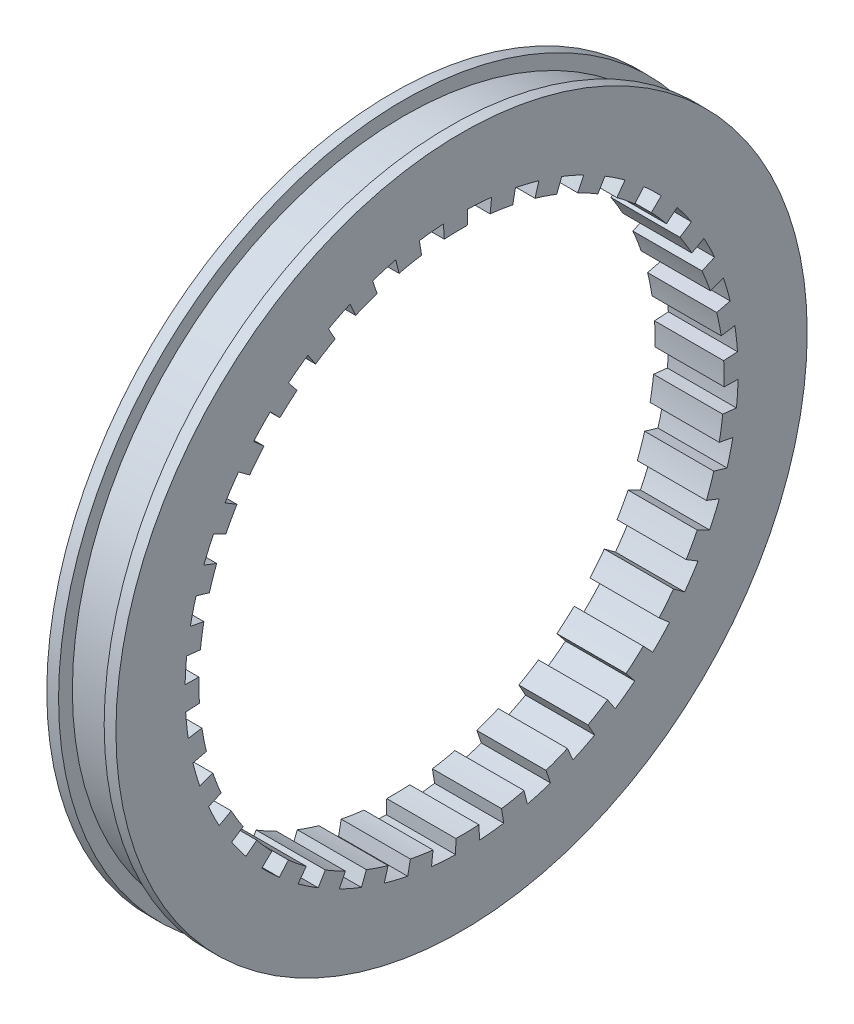
SolidWorks part; units mm, degrees
ref_plane "Front Plane" through (0, 0, 0) normal (0, 0, 1) x (1, 0, 0)
ref_plane "Top Plane" through (0, 0, 0) normal (0, 1, 0) x (1, 0, 0)
ref_plane "Right Plane" through (0, 0, 0) normal (1, 0, 0) x (0, 0, -1)
sketch "Sketch1" plane through (0, 0, 0) normal (1, 0, 0) x (0, 0, -1)
  circle A0 centre (0, 0) radius 20
  dimension "D1" = 40
extrude "Boss-Extrude1" add sketch "Sketch1" along normal blind 4
sketch "Sketch2" plane through (4, 0, 0) normal (1, 0, 0) x (0, 0, -1)
  line L0 (-17.0423, 8.4) -> (-17.9393, 8.8421)
  line L1 (-16.2453, 9.8534) -> (-17.1004, 10.372)
  circle A1 centre (0, 0) radius 20 construction
  circle A2 centre (0, 0) radius 19
  arc A3 (-16.2453, 9.8534) -> (-17.0423, 8.4) centre (0, 0) ccw
  arc A4 (-17.1004, 10.372) -> (-17.9393, 8.8421) centre (0, 0) ccw
  dimension "D2" = 5
  dimension "D1" = 1
extrude "Cut-Extrude1" cut sketch "Sketch2" against normal through all
sketch "Sketch3" plane through (4, 0, 0) normal (1, 0, 0) x (0, 0, -1)
  line L0 (-20, 0) -> (0, 0)
  arc A0 (-17.9393, 8.8421) -> (-17.1004, 10.372) centre (0, 0) ccw construction
ref_axis "Axis1" through (4, 0, 0) along (1, 0, 0)
pattern_circular "CirPattern2" count 36 over 360 about axis through (0, 0, 0) along (1, 0, 0) of "Cut-Extrude1"
sketch "Sketch5" plane through (4, 0, 0) normal (1, 0, 0) x (0, 0, -1)
  line L72 (-10.5591, 15.7958) -> (-11.1148, 16.6271)
  line L73 (-12.5217, 15.5951) -> (-11.8956, 14.8154)
  line L74 (-13.1416, 13.7222) -> (-13.8332, 14.4444)
  line L75 (-15.0395, 13.1838) -> (-14.2875, 12.5246)
  line L76 (-15.3248, 11.2317) -> (-16.1313, 11.8229)
  line L77 (-17.1004, 10.372) -> (-16.2453, 9.8534)
  line L78 (-17.0423, 8.4) -> (-17.9393, 8.8421)
  line L79 (-18.6416, 7.2449) -> (-17.7096, 6.8827)
  line L80 (-18.242, 5.313) -> (-19.2021, 5.5926)
  line L81 (-19.6165, 3.8978) -> (-18.6357, 3.7029)
  line L82 (-18.8875, 2.0646) -> (-19.8816, 2.1733)
  line L83 (-19.9953, 0.4322) -> (-18.9956, 0.4106)
  line L84 (-18.9591, -1.2466) -> (-19.9569, -1.3122)
  line L85 (-19.7666, -3.0465) -> (-18.7783, -2.8942)
  line L86 (-18.4546, -4.5198) -> (-19.4259, -4.7577)
  line L87 (-18.9373, -6.4327) -> (-17.9904, -6.111)
  line L88 (-17.3893, -7.6558) -> (-18.3046, -8.0587)
  line L89 (-17.5326, -9.6234) -> (-16.6559, -9.1422)
  line L90 (-15.7958, -10.5591) -> (-16.6271, -11.1148)
  line L91 (-15.5951, -12.5217) -> (-14.8154, -11.8956)
  line L92 (-13.7222, -13.1416) -> (-14.4444, -13.8332)
  line L93 (-13.1838, -15.0395) -> (-12.5246, -14.2875)
  line L94 (-11.2317, -15.3248) -> (-11.8229, -16.1313)
  line L95 (-10.372, -17.1004) -> (-9.8534, -16.2453)
  line L96 (-8.4, -17.0423) -> (-8.8421, -17.9393)
  line L97 (-7.2449, -18.6416) -> (-6.8827, -17.7096)
  line L98 (-5.313, -18.242) -> (-5.5926, -19.2021)
  line L99 (-3.8978, -19.6165) -> (-3.7029, -18.6357)
  line L100 (-2.0646, -18.8875) -> (-2.1733, -19.8816)
  line L101 (-0.4322, -19.9953) -> (-0.4106, -18.9956)
  line L102 (1.2466, -18.9591) -> (1.3122, -19.9569)
  line L103 (3.0465, -19.7666) -> (2.8942, -18.7783)
  line L104 (4.5198, -18.4546) -> (4.7577, -19.4259)
  line L105 (6.4327, -18.9373) -> (6.111, -17.9904)
  line L106 (7.6558, -17.3893) -> (8.0587, -18.3046)
  line L107 (9.6234, -17.5326) -> (9.1422, -16.6559)
  line L108 (10.5591, -15.7958) -> (11.1148, -16.6271)
  line L109 (12.5217, -15.5951) -> (11.8956, -14.8154)
  line L110 (13.1416, -13.7222) -> (13.8332, -14.4444)
  line L111 (15.0395, -13.1838) -> (14.2875, -12.5246)
  line L112 (15.3248, -11.2317) -> (16.1313, -11.8229)
  line L113 (17.1004, -10.372) -> (16.2453, -9.8534)
  line L114 (17.0423, -8.4) -> (17.9393, -8.8421)
  line L115 (18.6416, -7.2449) -> (17.7096, -6.8827)
  line L116 (18.242, -5.313) -> (19.2021, -5.5926)
  line L117 (19.6165, -3.8978) -> (18.6357, -3.7029)
  line L118 (18.8875, -2.0646) -> (19.8816, -2.1733)
  line L119 (19.9953, -0.4322) -> (18.9956, -0.4106)
  line L120 (18.9591, 1.2466) -> (19.9569, 1.3122)
  line L121 (19.7666, 3.0465) -> (18.7783, 2.8942)
  line L122 (18.4546, 4.5198) -> (19.4259, 4.7577)
  line L123 (18.9373, 6.4327) -> (17.9904, 6.111)
  line L124 (17.3893, 7.6558) -> (18.3046, 8.0587)
  line L125 (17.5326, 9.6234) -> (16.6559, 9.1422)
  line L126 (15.7958, 10.5591) -> (16.6271, 11.1148)
  line L127 (15.5951, 12.5217) -> (14.8154, 11.8956)
  line L128 (13.7222, 13.1416) -> (14.4444, 13.8332)
  line L129 (13.1838, 15.0395) -> (12.5246, 14.2875)
  line L130 (11.2317, 15.3248) -> (11.8229, 16.1313)
  line L131 (10.372, 17.1004) -> (9.8534, 16.2453)
  line L132 (8.4, 17.0423) -> (8.8421, 17.9393)
  line L133 (7.2449, 18.6416) -> (6.8827, 17.7096)
  line L134 (5.313, 18.242) -> (5.5926, 19.2021)
  line L135 (3.8978, 19.6165) -> (3.7029, 18.6357)
  line L136 (2.0646, 18.8875) -> (2.1733, 19.8816)
  line L137 (0.4322, 19.9953) -> (0.4106, 18.9956)
  line L138 (-1.2466, 18.9591) -> (-1.3122, 19.9569)
  line L139 (-3.0465, 19.7666) -> (-2.8942, 18.7783)
  line L140 (-4.5198, 18.4546) -> (-4.7577, 19.4259)
  line L141 (-6.4327, 18.9373) -> (-6.111, 17.9904)
  line L142 (-7.6558, 17.3893) -> (-8.0587, 18.3046)
  line L143 (-9.6234, 17.5326) -> (-9.1422, 16.6559)
  line L144 (-10.5591, 15.7958) -> (-11.1148, 16.6271)
  line L145 (-12.5217, 15.5951) -> (-11.8956, 14.8154)
  line L146 (-13.1416, 13.7222) -> (-13.8332, 14.4444)
  line L147 (-15.0395, 13.1838) -> (-14.2875, 12.5246)
  line L148 (-15.3248, 11.2317) -> (-16.1313, 11.8229)
  line L149 (-17.1004, 10.372) -> (-16.2453, 9.8534)
  line L150 (-17.0423, 8.4) -> (-17.9393, 8.8421)
  line L151 (-18.6416, 7.2449) -> (-17.7096, 6.8827)
  line L152 (-18.242, 5.313) -> (-19.2021, 5.5926)
  line L153 (-19.6165, 3.8978) -> (-18.6357, 3.7029)
  line L154 (-18.8875, 2.0646) -> (-19.8816, 2.1733)
  line L155 (-19.9953, 0.4322) -> (-18.9956, 0.4106)
  line L156 (-18.9591, -1.2466) -> (-19.9569, -1.3122)
  line L157 (-19.7666, -3.0465) -> (-18.7783, -2.8942)
  line L158 (-18.4546, -4.5198) -> (-19.4259, -4.7577)
  line L159 (-18.9373, -6.4327) -> (-17.9904, -6.111)
  line L160 (-17.3893, -7.6558) -> (-18.3046, -8.0587)
  line L161 (-17.5326, -9.6234) -> (-16.6559, -9.1422)
  line L162 (-15.7958, -10.5591) -> (-16.6271, -11.1148)
  line L163 (-15.5951, -12.5217) -> (-14.8154, -11.8956)
  line L164 (-13.7222, -13.1416) -> (-14.4444, -13.8332)
  line L165 (-13.1838, -15.0395) -> (-12.5246, -14.2875)
  line L166 (-11.2317, -15.3248) -> (-11.8229, -16.1313)
  line L167 (-10.372, -17.1004) -> (-9.8534, -16.2453)
  line L168 (-8.4, -17.0423) -> (-8.8421, -17.9393)
  line L169 (-7.2449, -18.6416) -> (-6.8827, -17.7096)
  line L170 (-5.313, -18.242) -> (-5.5926, -19.2021)
  line L171 (-3.8978, -19.6165) -> (-3.7029, -18.6357)
  line L172 (-2.0646, -18.8875) -> (-2.1733, -19.8816)
  line L173 (-0.4322, -19.9953) -> (-0.4106, -18.9956)
  line L174 (1.2466, -18.9591) -> (1.3122, -19.9569)
  line L175 (3.0465, -19.7666) -> (2.8942, -18.7783)
  line L176 (4.5198, -18.4546) -> (4.7577, -19.4259)
  line L177 (6.4327, -18.9373) -> (6.111, -17.9904)
  line L178 (7.6558, -17.3893) -> (8.0587, -18.3046)
  line L179 (9.6234, -17.5326) -> (9.1422, -16.6559)
  line L180 (10.5591, -15.7958) -> (11.1148, -16.6271)
  line L181 (12.5217, -15.5951) -> (11.8956, -14.8154)
  line L182 (13.1416, -13.7222) -> (13.8332, -14.4444)
  line L183 (15.0395, -13.1838) -> (14.2875, -12.5246)
  line L184 (15.3248, -11.2317) -> (16.1313, -11.8229)
  line L185 (17.1004, -10.372) -> (16.2453, -9.8534)
  line L186 (17.0423, -8.4) -> (17.9393, -8.8421)
  line L187 (18.6416, -7.2449) -> (17.7096, -6.8827)
  line L188 (18.242, -5.313) -> (19.2021, -5.5926)
  line L189 (19.6165, -3.8978) -> (18.6357, -3.7029)
  line L190 (18.8875, -2.0646) -> (19.8816, -2.1733)
  line L191 (19.9953, -0.4322) -> (18.9956, -0.4106)
  line L192 (18.9591, 1.2466) -> (19.9569, 1.3122)
  line L193 (19.7666, 3.0465) -> (18.7783, 2.8942)
  line L194 (18.4546, 4.5198) -> (19.4259, 4.7577)
  line L195 (18.9373, 6.4327) -> (17.9904, 6.111)
  line L196 (17.3893, 7.6558) -> (18.3046, 8.0587)
  line L197 (17.5326, 9.6234) -> (16.6559, 9.1422)
  line L198 (15.7958, 10.5591) -> (16.6271, 11.1148)
  line L199 (15.5951, 12.5217) -> (14.8154, 11.8956)
  line L200 (13.7222, 13.1416) -> (14.4444, 13.8332)
  line L201 (13.1838, 15.0395) -> (12.5246, 14.2875)
  line L202 (11.2317, 15.3248) -> (11.8229, 16.1313)
  line L203 (10.372, 17.1004) -> (9.8534, 16.2453)
  line L204 (8.4, 17.0423) -> (8.8421, 17.9393)
  line L205 (7.2449, 18.6416) -> (6.8827, 17.7096)
  line L206 (5.313, 18.242) -> (5.5926, 19.2021)
  line L207 (3.8978, 19.6165) -> (3.7029, 18.6357)
  line L208 (2.0646, 18.8875) -> (2.1733, 19.8816)
  line L209 (0.4322, 19.9953) -> (0.4106, 18.9956)
  line L210 (-1.2466, 18.9591) -> (-1.3122, 19.9569)
  line L211 (-3.0465, 19.7666) -> (-2.8942, 18.7783)
  line L212 (-4.5198, 18.4546) -> (-4.7577, 19.4259)
  line L213 (-6.4327, 18.9373) -> (-6.111, 17.9904)
  line L214 (-7.6558, 17.3893) -> (-8.0587, 18.3046)
  line L215 (-9.6234, 17.5326) -> (-9.1422, 16.6559)
  circle A1 centre (0, 0) radius 25
  arc A72 (-11.1148, 16.6271) -> (-12.5217, 15.5951) centre (0, 0) ccw
  arc A73 (-11.8956, 14.8154) -> (-13.1416, 13.7222) centre (0, 0) ccw
  arc A74 (-13.8332, 14.4444) -> (-15.0395, 13.1838) centre (0, 0) ccw
  arc A75 (-14.2875, 12.5246) -> (-15.3248, 11.2317) centre (0, 0) ccw
  arc A76 (-16.1313, 11.8229) -> (-17.1004, 10.372) centre (0, 0) ccw
  arc A77 (-16.2453, 9.8534) -> (-17.0423, 8.4) centre (0, 0) ccw
  arc A78 (-17.9393, 8.8421) -> (-18.6416, 7.2449) centre (0, 0) ccw
  arc A79 (-17.7096, 6.8827) -> (-18.242, 5.313) centre (0, 0) ccw
  arc A80 (-19.2021, 5.5926) -> (-19.6165, 3.8978) centre (0, 0) ccw
  arc A81 (-18.6357, 3.7029) -> (-18.8875, 2.0646) centre (0, 0) ccw
  arc A82 (-19.8816, 2.1733) -> (-19.9953, 0.4322) centre (0, 0) ccw
  arc A83 (-18.9956, 0.4106) -> (-18.9591, -1.2466) centre (0, 0) ccw
  arc A84 (-19.9569, -1.3122) -> (-19.7666, -3.0465) centre (0, 0) ccw
  arc A85 (-18.7783, -2.8942) -> (-18.4546, -4.5198) centre (0, 0) ccw
  arc A86 (-19.4259, -4.7577) -> (-18.9373, -6.4327) centre (0, 0) ccw
  arc A87 (-17.9904, -6.111) -> (-17.3893, -7.6558) centre (0, 0) ccw
  arc A88 (-18.3046, -8.0587) -> (-17.5326, -9.6234) centre (0, 0) ccw
  arc A89 (-16.6559, -9.1422) -> (-15.7958, -10.5591) centre (0, 0) ccw
  arc A90 (-16.6271, -11.1148) -> (-15.5951, -12.5217) centre (0, 0) ccw
  arc A91 (-14.8154, -11.8956) -> (-13.7222, -13.1416) centre (0, 0) ccw
  arc A92 (-14.4444, -13.8332) -> (-13.1838, -15.0395) centre (0, 0) ccw
  arc A93 (-12.5246, -14.2875) -> (-11.2317, -15.3248) centre (0, 0) ccw
  arc A94 (-11.8229, -16.1313) -> (-10.372, -17.1004) centre (0, 0) ccw
  arc A95 (-9.8534, -16.2453) -> (-8.4, -17.0423) centre (0, 0) ccw
  arc A96 (-8.8421, -17.9393) -> (-7.2449, -18.6416) centre (0, 0) ccw
  arc A97 (-6.8827, -17.7096) -> (-5.313, -18.242) centre (0, 0) ccw
  arc A98 (-5.5926, -19.2021) -> (-3.8978, -19.6165) centre (0, 0) ccw
  arc A99 (-3.7029, -18.6357) -> (-2.0646, -18.8875) centre (0, 0) ccw
  arc A100 (-2.1733, -19.8816) -> (-0.4322, -19.9953) centre (0, 0) ccw
  arc A101 (-0.4106, -18.9956) -> (1.2466, -18.9591) centre (0, 0) ccw
  arc A102 (1.3122, -19.9569) -> (3.0465, -19.7666) centre (0, 0) ccw
  arc A103 (2.8942, -18.7783) -> (4.5198, -18.4546) centre (0, 0) ccw
  arc A104 (4.7577, -19.4259) -> (6.4327, -18.9373) centre (0, 0) ccw
  arc A105 (6.111, -17.9904) -> (7.6558, -17.3893) centre (0, 0) ccw
  arc A106 (8.0587, -18.3046) -> (9.6234, -17.5326) centre (0, 0) ccw
  arc A107 (9.1422, -16.6559) -> (10.5591, -15.7958) centre (0, 0) ccw
  arc A108 (11.1148, -16.6271) -> (12.5217, -15.5951) centre (0, 0) ccw
  arc A109 (11.8956, -14.8154) -> (13.1416, -13.7222) centre (0, 0) ccw
  arc A110 (13.8332, -14.4444) -> (15.0395, -13.1838) centre (0, 0) ccw
  arc A111 (14.2875, -12.5246) -> (15.3248, -11.2317) centre (0, 0) ccw
  arc A112 (16.1313, -11.8229) -> (17.1004, -10.372) centre (0, 0) ccw
  arc A113 (16.2453, -9.8534) -> (17.0423, -8.4) centre (0, 0) ccw
  arc A114 (17.9393, -8.8421) -> (18.6416, -7.2449) centre (0, 0) ccw
  arc A115 (17.7096, -6.8827) -> (18.242, -5.313) centre (0, 0) ccw
  arc A116 (19.2021, -5.5926) -> (19.6165, -3.8978) centre (0, 0) ccw
  arc A117 (18.6357, -3.7029) -> (18.8875, -2.0646) centre (0, 0) ccw
  arc A118 (19.8816, -2.1733) -> (19.9953, -0.4322) centre (0, 0) ccw
  arc A119 (18.9956, -0.4106) -> (18.9591, 1.2466) centre (0, 0) ccw
  arc A120 (19.9569, 1.3122) -> (19.7666, 3.0465) centre (0, 0) ccw
  arc A121 (18.7783, 2.8942) -> (18.4546, 4.5198) centre (0, 0) ccw
  arc A122 (19.4259, 4.7577) -> (18.9373, 6.4327) centre (0, 0) ccw
  arc A123 (17.9904, 6.111) -> (17.3893, 7.6558) centre (0, 0) ccw
  arc A124 (18.3046, 8.0587) -> (17.5326, 9.6234) centre (0, 0) ccw
  arc A125 (16.6559, 9.1422) -> (15.7958, 10.5591) centre (0, 0) ccw
  arc A126 (16.6271, 11.1148) -> (15.5951, 12.5217) centre (0, 0) ccw
  arc A127 (14.8154, 11.8956) -> (13.7222, 13.1416) centre (0, 0) ccw
  arc A128 (14.4444, 13.8332) -> (13.1838, 15.0395) centre (0, 0) ccw
  arc A129 (12.5246, 14.2875) -> (11.2317, 15.3248) centre (0, 0) ccw
  arc A130 (11.8229, 16.1313) -> (10.372, 17.1004) centre (0, 0) ccw
  arc A131 (9.8534, 16.2453) -> (8.4, 17.0423) centre (0, 0) ccw
  arc A132 (8.8421, 17.9393) -> (7.2449, 18.6416) centre (0, 0) ccw
  arc A133 (6.8827, 17.7096) -> (5.313, 18.242) centre (0, 0) ccw
  arc A134 (5.5926, 19.2021) -> (3.8978, 19.6165) centre (0, 0) ccw
  arc A135 (3.7029, 18.6357) -> (2.0646, 18.8875) centre (0, 0) ccw
  arc A136 (2.1733, 19.8816) -> (0.4322, 19.9953) centre (0, 0) ccw
  arc A137 (0.4106, 18.9956) -> (-1.2466, 18.9591) centre (0, 0) ccw
  arc A138 (-1.3122, 19.9569) -> (-3.0465, 19.7666) centre (0, 0) ccw
  arc A139 (-2.8942, 18.7783) -> (-4.5198, 18.4546) centre (0, 0) ccw
  arc A140 (-4.7577, 19.4259) -> (-6.4327, 18.9373) centre (0, 0) ccw
  arc A141 (-6.111, 17.9904) -> (-7.6558, 17.3893) centre (0, 0) ccw
  arc A142 (-8.0587, 18.3046) -> (-9.6234, 17.5326) centre (0, 0) ccw
  arc A143 (-9.1422, 16.6559) -> (-10.5591, 15.7958) centre (0, 0) ccw
  arc A144 (-11.1148, 16.6271) -> (-12.5217, 15.5951) centre (0, 0) ccw
  arc A145 (-11.8956, 14.8154) -> (-13.1416, 13.7222) centre (0, 0) ccw
  arc A146 (-13.8332, 14.4444) -> (-15.0395, 13.1838) centre (0, 0) ccw
  arc A147 (-14.2875, 12.5246) -> (-15.3248, 11.2317) centre (0, 0) ccw
  arc A148 (-16.1313, 11.8229) -> (-17.1004, 10.372) centre (0, 0) ccw
  arc A149 (-16.2453, 9.8534) -> (-17.0423, 8.4) centre (0, 0) ccw
  arc A150 (-17.9393, 8.8421) -> (-18.6416, 7.2449) centre (0, 0) ccw
  arc A151 (-17.7096, 6.8827) -> (-18.242, 5.313) centre (0, 0) ccw
  arc A152 (-19.2021, 5.5926) -> (-19.6165, 3.8978) centre (0, 0) ccw
  arc A153 (-18.6357, 3.7029) -> (-18.8875, 2.0646) centre (0, 0) ccw
  arc A154 (-19.8816, 2.1733) -> (-19.9953, 0.4322) centre (0, 0) ccw
  arc A155 (-18.9956, 0.4106) -> (-18.9591, -1.2466) centre (0, 0) ccw
  arc A156 (-19.9569, -1.3122) -> (-19.7666, -3.0465) centre (0, 0) ccw
  arc A157 (-18.7783, -2.8942) -> (-18.4546, -4.5198) centre (0, 0) ccw
  arc A158 (-19.4259, -4.7577) -> (-18.9373, -6.4327) centre (0, 0) ccw
  arc A159 (-17.9904, -6.111) -> (-17.3893, -7.6558) centre (0, 0) ccw
  arc A160 (-18.3046, -8.0587) -> (-17.5326, -9.6234) centre (0, 0) ccw
  arc A161 (-16.6559, -9.1422) -> (-15.7958, -10.5591) centre (0, 0) ccw
  arc A162 (-16.6271, -11.1148) -> (-15.5951, -12.5217) centre (0, 0) ccw
  arc A163 (-14.8154, -11.8956) -> (-13.7222, -13.1416) centre (0, 0) ccw
  arc A164 (-14.4444, -13.8332) -> (-13.1838, -15.0395) centre (0, 0) ccw
  arc A165 (-12.5246, -14.2875) -> (-11.2317, -15.3248) centre (0, 0) ccw
  arc A166 (-11.8229, -16.1313) -> (-10.372, -17.1004) centre (0, 0) ccw
  arc A167 (-9.8534, -16.2453) -> (-8.4, -17.0423) centre (0, 0) ccw
  arc A168 (-8.8421, -17.9393) -> (-7.2449, -18.6416) centre (0, 0) ccw
  arc A169 (-6.8827, -17.7096) -> (-5.313, -18.242) centre (0, 0) ccw
  arc A170 (-5.5926, -19.2021) -> (-3.8978, -19.6165) centre (0, 0) ccw
  arc A171 (-3.7029, -18.6357) -> (-2.0646, -18.8875) centre (0, 0) ccw
  arc A172 (-2.1733, -19.8816) -> (-0.4322, -19.9953) centre (0, 0) ccw
  arc A173 (-0.4106, -18.9956) -> (1.2466, -18.9591) centre (0, 0) ccw
  arc A174 (1.3122, -19.9569) -> (3.0465, -19.7666) centre (0, 0) ccw
  arc A175 (2.8942, -18.7783) -> (4.5198, -18.4546) centre (0, 0) ccw
  arc A176 (4.7577, -19.4259) -> (6.4327, -18.9373) centre (0, 0) ccw
  arc A177 (6.111, -17.9904) -> (7.6558, -17.3893) centre (0, 0) ccw
  arc A178 (8.0587, -18.3046) -> (9.6234, -17.5326) centre (0, 0) ccw
  arc A179 (9.1422, -16.6559) -> (10.5591, -15.7958) centre (0, 0) ccw
  arc A180 (11.1148, -16.6271) -> (12.5217, -15.5951) centre (0, 0) ccw
  arc A181 (11.8956, -14.8154) -> (13.1416, -13.7222) centre (0, 0) ccw
  arc A182 (13.8332, -14.4444) -> (15.0395, -13.1838) centre (0, 0) ccw
  arc A183 (14.2875, -12.5246) -> (15.3248, -11.2317) centre (0, 0) ccw
  arc A184 (16.1313, -11.8229) -> (17.1004, -10.372) centre (0, 0) ccw
  arc A185 (16.2453, -9.8534) -> (17.0423, -8.4) centre (0, 0) ccw
  arc A186 (17.9393, -8.8421) -> (18.6416, -7.2449) centre (0, 0) ccw
  arc A187 (17.7096, -6.8827) -> (18.242, -5.313) centre (0, 0) ccw
  arc A188 (19.2021, -5.5926) -> (19.6165, -3.8978) centre (0, 0) ccw
  arc A189 (18.6357, -3.7029) -> (18.8875, -2.0646) centre (0, 0) ccw
  arc A190 (19.8816, -2.1733) -> (19.9953, -0.4322) centre (0, 0) ccw
  arc A191 (18.9956, -0.4106) -> (18.9591, 1.2466) centre (0, 0) ccw
  arc A192 (19.9569, 1.3122) -> (19.7666, 3.0465) centre (0, 0) ccw
  arc A193 (18.7783, 2.8942) -> (18.4546, 4.5198) centre (0, 0) ccw
  arc A194 (19.4259, 4.7577) -> (18.9373, 6.4327) centre (0, 0) ccw
  arc A195 (17.9904, 6.111) -> (17.3893, 7.6558) centre (0, 0) ccw
  arc A196 (18.3046, 8.0587) -> (17.5326, 9.6234) centre (0, 0) ccw
  arc A197 (16.6559, 9.1422) -> (15.7958, 10.5591) centre (0, 0) ccw
  arc A198 (16.6271, 11.1148) -> (15.5951, 12.5217) centre (0, 0) ccw
  arc A199 (14.8154, 11.8956) -> (13.7222, 13.1416) centre (0, 0) ccw
  arc A200 (14.4444, 13.8332) -> (13.1838, 15.0395) centre (0, 0) ccw
  arc A201 (12.5246, 14.2875) -> (11.2317, 15.3248) centre (0, 0) ccw
  arc A202 (11.8229, 16.1313) -> (10.372, 17.1004) centre (0, 0) ccw
  arc A203 (9.8534, 16.2453) -> (8.4, 17.0423) centre (0, 0) ccw
  arc A204 (8.8421, 17.9393) -> (7.2449, 18.6416) centre (0, 0) ccw
  arc A205 (6.8827, 17.7096) -> (5.313, 18.242) centre (0, 0) ccw
  arc A206 (5.5926, 19.2021) -> (3.8978, 19.6165) centre (0, 0) ccw
  arc A207 (3.7029, 18.6357) -> (2.0646, 18.8875) centre (0, 0) ccw
  arc A208 (2.1733, 19.8816) -> (0.4322, 19.9953) centre (0, 0) ccw
  arc A209 (0.4106, 18.9956) -> (-1.2466, 18.9591) centre (0, 0) ccw
  arc A210 (-1.3122, 19.9569) -> (-3.0465, 19.7666) centre (0, 0) ccw
  arc A211 (-2.8942, 18.7783) -> (-4.5198, 18.4546) centre (0, 0) ccw
  arc A212 (-4.7577, 19.4259) -> (-6.4327, 18.9373) centre (0, 0) ccw
  arc A213 (-6.111, 17.9904) -> (-7.6558, 17.3893) centre (0, 0) ccw
  arc A214 (-8.0587, 18.3046) -> (-9.6234, 17.5326) centre (0, 0) ccw
  arc A215 (-9.1422, 16.6559) -> (-10.5591, 15.7958) centre (0, 0) ccw
  dimension "D1" = 0
extrude "Boss-Extrude2" add sketch "Sketch5" along normal blind 5 separate body
sketch "Sketch6" plane through (9, 0, 0) normal (1, 0, 0) x (0, 0, -1)
  line L72 (-10.5591, 15.7958) -> (-11.1148, 16.6271)
  line L73 (-12.5217, 15.5951) -> (-11.8956, 14.8154)
  line L74 (-13.1416, 13.7222) -> (-13.8332, 14.4444)
  line L75 (-15.0395, 13.1838) -> (-14.2875, 12.5246)
  line L76 (-15.3248, 11.2317) -> (-16.1313, 11.8229)
  line L77 (-17.1004, 10.372) -> (-16.2453, 9.8534)
  line L78 (-17.0423, 8.4) -> (-17.9393, 8.8421)
  line L79 (-18.6416, 7.2449) -> (-17.7096, 6.8827)
  line L80 (-18.242, 5.313) -> (-19.2021, 5.5926)
  line L81 (-19.6165, 3.8978) -> (-18.6357, 3.7029)
  line L82 (-18.8875, 2.0646) -> (-19.8816, 2.1733)
  line L83 (-19.9953, 0.4322) -> (-18.9956, 0.4106)
  line L84 (-18.9591, -1.2466) -> (-19.9569, -1.3122)
  line L85 (-19.7666, -3.0465) -> (-18.7783, -2.8942)
  line L86 (-18.4546, -4.5198) -> (-19.4259, -4.7577)
  line L87 (-18.9373, -6.4327) -> (-17.9904, -6.111)
  line L88 (-17.3893, -7.6558) -> (-18.3046, -8.0587)
  line L89 (-17.5326, -9.6234) -> (-16.6559, -9.1422)
  line L90 (-15.7958, -10.5591) -> (-16.6271, -11.1148)
  line L91 (-15.5951, -12.5217) -> (-14.8154, -11.8956)
  line L92 (-13.7222, -13.1416) -> (-14.4444, -13.8332)
  line L93 (-13.1838, -15.0395) -> (-12.5246, -14.2875)
  line L94 (-11.2317, -15.3248) -> (-11.8229, -16.1313)
  line L95 (-10.372, -17.1004) -> (-9.8534, -16.2453)
  line L96 (-8.4, -17.0423) -> (-8.8421, -17.9393)
  line L97 (-7.2449, -18.6416) -> (-6.8827, -17.7096)
  line L98 (-5.313, -18.242) -> (-5.5926, -19.2021)
  line L99 (-3.8978, -19.6165) -> (-3.7029, -18.6357)
  line L100 (-2.0646, -18.8875) -> (-2.1733, -19.8816)
  line L101 (-0.4322, -19.9953) -> (-0.4106, -18.9956)
  line L102 (1.2466, -18.9591) -> (1.3122, -19.9569)
  line L103 (3.0465, -19.7666) -> (2.8942, -18.7783)
  line L104 (4.5198, -18.4546) -> (4.7577, -19.4259)
  line L105 (6.4327, -18.9373) -> (6.111, -17.9904)
  line L106 (7.6558, -17.3893) -> (8.0587, -18.3046)
  line L107 (9.6234, -17.5326) -> (9.1422, -16.6559)
  line L108 (10.5591, -15.7958) -> (11.1148, -16.6271)
  line L109 (12.5217, -15.5951) -> (11.8956, -14.8154)
  line L110 (13.1416, -13.7222) -> (13.8332, -14.4444)
  line L111 (15.0395, -13.1838) -> (14.2875, -12.5246)
  line L112 (15.3248, -11.2317) -> (16.1313, -11.8229)
  line L113 (17.1004, -10.372) -> (16.2453, -9.8534)
  line L114 (17.0423, -8.4) -> (17.9393, -8.8421)
  line L115 (18.6416, -7.2449) -> (17.7096, -6.8827)
  line L116 (18.242, -5.313) -> (19.2021, -5.5926)
  line L117 (19.6165, -3.8978) -> (18.6357, -3.7029)
  line L118 (18.8875, -2.0646) -> (19.8816, -2.1733)
  line L119 (19.9953, -0.4322) -> (18.9956, -0.4106)
  line L120 (18.9591, 1.2466) -> (19.9569, 1.3122)
  line L121 (19.7666, 3.0465) -> (18.7783, 2.8942)
  line L122 (18.4546, 4.5198) -> (19.4259, 4.7577)
  line L123 (18.9373, 6.4327) -> (17.9904, 6.111)
  line L124 (17.3893, 7.6558) -> (18.3046, 8.0587)
  line L125 (17.5326, 9.6234) -> (16.6559, 9.1422)
  line L126 (15.7958, 10.5591) -> (16.6271, 11.1148)
  line L127 (15.5951, 12.5217) -> (14.8154, 11.8956)
  line L128 (13.7222, 13.1416) -> (14.4444, 13.8332)
  line L129 (13.1838, 15.0395) -> (12.5246, 14.2875)
  line L130 (11.2317, 15.3248) -> (11.8229, 16.1313)
  line L131 (10.372, 17.1004) -> (9.8534, 16.2453)
  line L132 (8.4, 17.0423) -> (8.8421, 17.9393)
  line L133 (7.2449, 18.6416) -> (6.8827, 17.7096)
  line L134 (5.313, 18.242) -> (5.5926, 19.2021)
  line L135 (3.8978, 19.6165) -> (3.7029, 18.6357)
  line L136 (2.0646, 18.8875) -> (2.1733, 19.8816)
  line L137 (0.4322, 19.9953) -> (0.4106, 18.9956)
  line L138 (-1.2466, 18.9591) -> (-1.3122, 19.9569)
  line L139 (-3.0465, 19.7666) -> (-2.8942, 18.7783)
  line L140 (-4.5198, 18.4546) -> (-4.7577, 19.4259)
  line L141 (-6.4327, 18.9373) -> (-6.111, 17.9904)
  line L142 (-7.6558, 17.3893) -> (-8.0587, 18.3046)
  line L143 (-9.6234, 17.5326) -> (-9.1422, 16.6559)
  line L144 (-10.5591, 15.7958) -> (-11.1148, 16.6271)
  line L145 (-12.5217, 15.5951) -> (-11.8956, 14.8154)
  line L146 (-13.1416, 13.7222) -> (-13.8332, 14.4444)
  line L147 (-15.0395, 13.1838) -> (-14.2875, 12.5246)
  line L148 (-15.3248, 11.2317) -> (-16.1313, 11.8229)
  line L149 (-17.1004, 10.372) -> (-16.2453, 9.8534)
  line L150 (-17.0423, 8.4) -> (-17.9393, 8.8421)
  line L151 (-18.6416, 7.2449) -> (-17.7096, 6.8827)
  line L152 (-18.242, 5.313) -> (-19.2021, 5.5926)
  line L153 (-19.6165, 3.8978) -> (-18.6357, 3.7029)
  line L154 (-18.8875, 2.0646) -> (-19.8816, 2.1733)
  line L155 (-19.9953, 0.4322) -> (-18.9956, 0.4106)
  line L156 (-18.9591, -1.2466) -> (-19.9569, -1.3122)
  line L157 (-19.7666, -3.0465) -> (-18.7783, -2.8942)
  line L158 (-18.4546, -4.5198) -> (-19.4259, -4.7577)
  line L159 (-18.9373, -6.4327) -> (-17.9904, -6.111)
  line L160 (-17.3893, -7.6558) -> (-18.3046, -8.0587)
  line L161 (-17.5326, -9.6234) -> (-16.6559, -9.1422)
  line L162 (-15.7958, -10.5591) -> (-16.6271, -11.1148)
  line L163 (-15.5951, -12.5217) -> (-14.8154, -11.8956)
  line L164 (-13.7222, -13.1416) -> (-14.4444, -13.8332)
  line L165 (-13.1838, -15.0395) -> (-12.5246, -14.2875)
  line L166 (-11.2317, -15.3248) -> (-11.8229, -16.1313)
  line L167 (-10.372, -17.1004) -> (-9.8534, -16.2453)
  line L168 (-8.4, -17.0423) -> (-8.8421, -17.9393)
  line L169 (-7.2449, -18.6416) -> (-6.8827, -17.7096)
  line L170 (-5.313, -18.242) -> (-5.5926, -19.2021)
  line L171 (-3.8978, -19.6165) -> (-3.7029, -18.6357)
  line L172 (-2.0646, -18.8875) -> (-2.1733, -19.8816)
  line L173 (-0.4322, -19.9953) -> (-0.4106, -18.9956)
  line L174 (1.2466, -18.9591) -> (1.3122, -19.9569)
  line L175 (3.0465, -19.7666) -> (2.8942, -18.7783)
  line L176 (4.5198, -18.4546) -> (4.7577, -19.4259)
  line L177 (6.4327, -18.9373) -> (6.111, -17.9904)
  line L178 (7.6558, -17.3893) -> (8.0587, -18.3046)
  line L179 (9.6234, -17.5326) -> (9.1422, -16.6559)
  line L180 (10.5591, -15.7958) -> (11.1148, -16.6271)
  line L181 (12.5217, -15.5951) -> (11.8956, -14.8154)
  line L182 (13.1416, -13.7222) -> (13.8332, -14.4444)
  line L183 (15.0395, -13.1838) -> (14.2875, -12.5246)
  line L184 (15.3248, -11.2317) -> (16.1313, -11.8229)
  line L185 (17.1004, -10.372) -> (16.2453, -9.8534)
  line L186 (17.0423, -8.4) -> (17.9393, -8.8421)
  line L187 (18.6416, -7.2449) -> (17.7096, -6.8827)
  line L188 (18.242, -5.313) -> (19.2021, -5.5926)
  line L189 (19.6165, -3.8978) -> (18.6357, -3.7029)
  line L190 (18.8875, -2.0646) -> (19.8816, -2.1733)
  line L191 (19.9953, -0.4322) -> (18.9956, -0.4106)
  line L192 (18.9591, 1.2466) -> (19.9569, 1.3122)
  line L193 (19.7666, 3.0465) -> (18.7783, 2.8942)
  line L194 (18.4546, 4.5198) -> (19.4259, 4.7577)
  line L195 (18.9373, 6.4327) -> (17.9904, 6.111)
  line L196 (17.3893, 7.6558) -> (18.3046, 8.0587)
  line L197 (17.5326, 9.6234) -> (16.6559, 9.1422)
  line L198 (15.7958, 10.5591) -> (16.6271, 11.1148)
  line L199 (15.5951, 12.5217) -> (14.8154, 11.8956)
  line L200 (13.7222, 13.1416) -> (14.4444, 13.8332)
  line L201 (13.1838, 15.0395) -> (12.5246, 14.2875)
  line L202 (11.2317, 15.3248) -> (11.8229, 16.1313)
  line L203 (10.372, 17.1004) -> (9.8534, 16.2453)
  line L204 (8.4, 17.0423) -> (8.8421, 17.9393)
  line L205 (7.2449, 18.6416) -> (6.8827, 17.7096)
  line L206 (5.313, 18.242) -> (5.5926, 19.2021)
  line L207 (3.8978, 19.6165) -> (3.7029, 18.6357)
  line L208 (2.0646, 18.8875) -> (2.1733, 19.8816)
  line L209 (0.4322, 19.9953) -> (0.4106, 18.9956)
  line L210 (-1.2466, 18.9591) -> (-1.3122, 19.9569)
  line L211 (-3.0465, 19.7666) -> (-2.8942, 18.7783)
  line L212 (-4.5198, 18.4546) -> (-4.7577, 19.4259)
  line L213 (-6.4327, 18.9373) -> (-6.111, 17.9904)
  line L214 (-7.6558, 17.3893) -> (-8.0587, 18.3046)
  line L215 (-9.6234, 17.5326) -> (-9.1422, 16.6559)
  arc A73 (-11.1148, 16.6271) -> (-12.5217, 15.5951) centre (0, 0) ccw
  arc A74 (-11.8956, 14.8154) -> (-13.1416, 13.7222) centre (0, 0) ccw
  arc A75 (-13.8332, 14.4444) -> (-15.0395, 13.1838) centre (0, 0) ccw
  arc A76 (-14.2875, 12.5246) -> (-15.3248, 11.2317) centre (0, 0) ccw
  arc A77 (-16.1313, 11.8229) -> (-17.1004, 10.372) centre (0, 0) ccw
  arc A78 (-16.2453, 9.8534) -> (-17.0423, 8.4) centre (0, 0) ccw
  arc A79 (-17.9393, 8.8421) -> (-18.6416, 7.2449) centre (0, 0) ccw
  arc A80 (-17.7096, 6.8827) -> (-18.242, 5.313) centre (0, 0) ccw
  arc A81 (-19.2021, 5.5926) -> (-19.6165, 3.8978) centre (0, 0) ccw
  arc A82 (-18.6357, 3.7029) -> (-18.8875, 2.0646) centre (0, 0) ccw
  arc A83 (-19.8816, 2.1733) -> (-19.9953, 0.4322) centre (0, 0) ccw
  arc A84 (-18.9956, 0.4106) -> (-18.9591, -1.2466) centre (0, 0) ccw
  arc A85 (-19.9569, -1.3122) -> (-19.7666, -3.0465) centre (0, 0) ccw
  arc A86 (-18.7783, -2.8942) -> (-18.4546, -4.5198) centre (0, 0) ccw
  arc A87 (-19.4259, -4.7577) -> (-18.9373, -6.4327) centre (0, 0) ccw
  arc A88 (-17.9904, -6.111) -> (-17.3893, -7.6558) centre (0, 0) ccw
  arc A89 (-18.3046, -8.0587) -> (-17.5326, -9.6234) centre (0, 0) ccw
  arc A90 (-16.6559, -9.1422) -> (-15.7958, -10.5591) centre (0, 0) ccw
  arc A91 (-16.6271, -11.1148) -> (-15.5951, -12.5217) centre (0, 0) ccw
  arc A92 (-14.8154, -11.8956) -> (-13.7222, -13.1416) centre (0, 0) ccw
  arc A93 (-14.4444, -13.8332) -> (-13.1838, -15.0395) centre (0, 0) ccw
  arc A94 (-12.5246, -14.2875) -> (-11.2317, -15.3248) centre (0, 0) ccw
  arc A95 (-11.8229, -16.1313) -> (-10.372, -17.1004) centre (0, 0) ccw
  arc A96 (-9.8534, -16.2453) -> (-8.4, -17.0423) centre (0, 0) ccw
  arc A97 (-8.8421, -17.9393) -> (-7.2449, -18.6416) centre (0, 0) ccw
  arc A98 (-6.8827, -17.7096) -> (-5.313, -18.242) centre (0, 0) ccw
  arc A99 (-5.5926, -19.2021) -> (-3.8978, -19.6165) centre (0, 0) ccw
  arc A100 (-3.7029, -18.6357) -> (-2.0646, -18.8875) centre (0, 0) ccw
  arc A101 (-2.1733, -19.8816) -> (-0.4322, -19.9953) centre (0, 0) ccw
  arc A102 (-0.4106, -18.9956) -> (1.2466, -18.9591) centre (0, 0) ccw
  arc A103 (1.3122, -19.9569) -> (3.0465, -19.7666) centre (0, 0) ccw
  arc A104 (2.8942, -18.7783) -> (4.5198, -18.4546) centre (0, 0) ccw
  arc A105 (4.7577, -19.4259) -> (6.4327, -18.9373) centre (0, 0) ccw
  arc A106 (6.111, -17.9904) -> (7.6558, -17.3893) centre (0, 0) ccw
  arc A107 (8.0587, -18.3046) -> (9.6234, -17.5326) centre (0, 0) ccw
  arc A108 (9.1422, -16.6559) -> (10.5591, -15.7958) centre (0, 0) ccw
  arc A109 (11.1148, -16.6271) -> (12.5217, -15.5951) centre (0, 0) ccw
  arc A110 (11.8956, -14.8154) -> (13.1416, -13.7222) centre (0, 0) ccw
  arc A111 (13.8332, -14.4444) -> (15.0395, -13.1838) centre (0, 0) ccw
  arc A112 (14.2875, -12.5246) -> (15.3248, -11.2317) centre (0, 0) ccw
  arc A113 (16.1313, -11.8229) -> (17.1004, -10.372) centre (0, 0) ccw
  arc A114 (16.2453, -9.8534) -> (17.0423, -8.4) centre (0, 0) ccw
  arc A115 (17.9393, -8.8421) -> (18.6416, -7.2449) centre (0, 0) ccw
  arc A116 (17.7096, -6.8827) -> (18.242, -5.313) centre (0, 0) ccw
  arc A117 (19.2021, -5.5926) -> (19.6165, -3.8978) centre (0, 0) ccw
  arc A118 (18.6357, -3.7029) -> (18.8875, -2.0646) centre (0, 0) ccw
  arc A119 (19.8816, -2.1733) -> (19.9953, -0.4322) centre (0, 0) ccw
  arc A120 (18.9956, -0.4106) -> (18.9591, 1.2466) centre (0, 0) ccw
  arc A121 (19.9569, 1.3122) -> (19.7666, 3.0465) centre (0, 0) ccw
  arc A122 (18.7783, 2.8942) -> (18.4546, 4.5198) centre (0, 0) ccw
  arc A123 (19.4259, 4.7577) -> (18.9373, 6.4327) centre (0, 0) ccw
  arc A124 (17.9904, 6.111) -> (17.3893, 7.6558) centre (0, 0) ccw
  arc A125 (18.3046, 8.0587) -> (17.5326, 9.6234) centre (0, 0) ccw
  arc A126 (16.6559, 9.1422) -> (15.7958, 10.5591) centre (0, 0) ccw
  arc A127 (16.6271, 11.1148) -> (15.5951, 12.5217) centre (0, 0) ccw
  arc A128 (14.8154, 11.8956) -> (13.7222, 13.1416) centre (0, 0) ccw
  arc A129 (14.4444, 13.8332) -> (13.1838, 15.0395) centre (0, 0) ccw
  arc A130 (12.5246, 14.2875) -> (11.2317, 15.3248) centre (0, 0) ccw
  arc A131 (11.8229, 16.1313) -> (10.372, 17.1004) centre (0, 0) ccw
  arc A132 (9.8534, 16.2453) -> (8.4, 17.0423) centre (0, 0) ccw
  arc A133 (8.8421, 17.9393) -> (7.2449, 18.6416) centre (0, 0) ccw
  arc A134 (6.8827, 17.7096) -> (5.313, 18.242) centre (0, 0) ccw
  arc A135 (5.5926, 19.2021) -> (3.8978, 19.6165) centre (0, 0) ccw
  arc A136 (3.7029, 18.6357) -> (2.0646, 18.8875) centre (0, 0) ccw
  arc A137 (2.1733, 19.8816) -> (0.4322, 19.9953) centre (0, 0) ccw
  arc A138 (0.4106, 18.9956) -> (-1.2466, 18.9591) centre (0, 0) ccw
  arc A139 (-1.3122, 19.9569) -> (-3.0465, 19.7666) centre (0, 0) ccw
  arc A140 (-2.8942, 18.7783) -> (-4.5198, 18.4546) centre (0, 0) ccw
  arc A141 (-4.7577, 19.4259) -> (-6.4327, 18.9373) centre (0, 0) ccw
  arc A142 (-6.111, 17.9904) -> (-7.6558, 17.3893) centre (0, 0) ccw
  arc A143 (-8.0587, 18.3046) -> (-9.6234, 17.5326) centre (0, 0) ccw
  arc A144 (-9.1422, 16.6559) -> (-10.5591, 15.7958) centre (0, 0) ccw
  arc A145 (-11.1148, 16.6271) -> (-12.5217, 15.5951) centre (0, 0) ccw
  arc A146 (-11.8956, 14.8154) -> (-13.1416, 13.7222) centre (0, 0) ccw
  arc A147 (-13.8332, 14.4444) -> (-15.0395, 13.1838) centre (0, 0) ccw
  arc A148 (-14.2875, 12.5246) -> (-15.3248, 11.2317) centre (0, 0) ccw
  arc A149 (-16.1313, 11.8229) -> (-17.1004, 10.372) centre (0, 0) ccw
  arc A150 (-16.2453, 9.8534) -> (-17.0423, 8.4) centre (0, 0) ccw
  arc A151 (-17.9393, 8.8421) -> (-18.6416, 7.2449) centre (0, 0) ccw
  arc A152 (-17.7096, 6.8827) -> (-18.242, 5.313) centre (0, 0) ccw
  arc A153 (-19.2021, 5.5926) -> (-19.6165, 3.8978) centre (0, 0) ccw
  arc A154 (-18.6357, 3.7029) -> (-18.8875, 2.0646) centre (0, 0) ccw
  arc A155 (-19.8816, 2.1733) -> (-19.9953, 0.4322) centre (0, 0) ccw
  arc A156 (-18.9956, 0.4106) -> (-18.9591, -1.2466) centre (0, 0) ccw
  arc A157 (-19.9569, -1.3122) -> (-19.7666, -3.0465) centre (0, 0) ccw
  arc A158 (-18.7783, -2.8942) -> (-18.4546, -4.5198) centre (0, 0) ccw
  arc A159 (-19.4259, -4.7577) -> (-18.9373, -6.4327) centre (0, 0) ccw
  arc A160 (-17.9904, -6.111) -> (-17.3893, -7.6558) centre (0, 0) ccw
  arc A161 (-18.3046, -8.0587) -> (-17.5326, -9.6234) centre (0, 0) ccw
  arc A162 (-16.6559, -9.1422) -> (-15.7958, -10.5591) centre (0, 0) ccw
  arc A163 (-16.6271, -11.1148) -> (-15.5951, -12.5217) centre (0, 0) ccw
  arc A164 (-14.8154, -11.8956) -> (-13.7222, -13.1416) centre (0, 0) ccw
  arc A165 (-14.4444, -13.8332) -> (-13.1838, -15.0395) centre (0, 0) ccw
  arc A166 (-12.5246, -14.2875) -> (-11.2317, -15.3248) centre (0, 0) ccw
  arc A167 (-11.8229, -16.1313) -> (-10.372, -17.1004) centre (0, 0) ccw
  arc A168 (-9.8534, -16.2453) -> (-8.4, -17.0423) centre (0, 0) ccw
  arc A169 (-8.8421, -17.9393) -> (-7.2449, -18.6416) centre (0, 0) ccw
  arc A170 (-6.8827, -17.7096) -> (-5.313, -18.242) centre (0, 0) ccw
  arc A171 (-5.5926, -19.2021) -> (-3.8978, -19.6165) centre (0, 0) ccw
  arc A172 (-3.7029, -18.6357) -> (-2.0646, -18.8875) centre (0, 0) ccw
  arc A173 (-2.1733, -19.8816) -> (-0.4322, -19.9953) centre (0, 0) ccw
  arc A174 (-0.4106, -18.9956) -> (1.2466, -18.9591) centre (0, 0) ccw
  arc A175 (1.3122, -19.9569) -> (3.0465, -19.7666) centre (0, 0) ccw
  arc A176 (2.8942, -18.7783) -> (4.5198, -18.4546) centre (0, 0) ccw
  arc A177 (4.7577, -19.4259) -> (6.4327, -18.9373) centre (0, 0) ccw
  arc A178 (6.111, -17.9904) -> (7.6558, -17.3893) centre (0, 0) ccw
  arc A179 (8.0587, -18.3046) -> (9.6234, -17.5326) centre (0, 0) ccw
  arc A180 (9.1422, -16.6559) -> (10.5591, -15.7958) centre (0, 0) ccw
  arc A181 (11.1148, -16.6271) -> (12.5217, -15.5951) centre (0, 0) ccw
  arc A182 (11.8956, -14.8154) -> (13.1416, -13.7222) centre (0, 0) ccw
  arc A183 (13.8332, -14.4444) -> (15.0395, -13.1838) centre (0, 0) ccw
  arc A184 (14.2875, -12.5246) -> (15.3248, -11.2317) centre (0, 0) ccw
  arc A185 (16.1313, -11.8229) -> (17.1004, -10.372) centre (0, 0) ccw
  arc A186 (16.2453, -9.8534) -> (17.0423, -8.4) centre (0, 0) ccw
  arc A187 (17.9393, -8.8421) -> (18.6416, -7.2449) centre (0, 0) ccw
  arc A188 (17.7096, -6.8827) -> (18.242, -5.313) centre (0, 0) ccw
  arc A189 (19.2021, -5.5926) -> (19.6165, -3.8978) centre (0, 0) ccw
  arc A190 (18.6357, -3.7029) -> (18.8875, -2.0646) centre (0, 0) ccw
  arc A191 (19.8816, -2.1733) -> (19.9953, -0.4322) centre (0, 0) ccw
  arc A192 (18.9956, -0.4106) -> (18.9591, 1.2466) centre (0, 0) ccw
  arc A193 (19.9569, 1.3122) -> (19.7666, 3.0465) centre (0, 0) ccw
  arc A194 (18.7783, 2.8942) -> (18.4546, 4.5198) centre (0, 0) ccw
  arc A195 (19.4259, 4.7577) -> (18.9373, 6.4327) centre (0, 0) ccw
  arc A196 (17.9904, 6.111) -> (17.3893, 7.6558) centre (0, 0) ccw
  arc A197 (18.3046, 8.0587) -> (17.5326, 9.6234) centre (0, 0) ccw
  arc A198 (16.6559, 9.1422) -> (15.7958, 10.5591) centre (0, 0) ccw
  arc A199 (16.6271, 11.1148) -> (15.5951, 12.5217) centre (0, 0) ccw
  arc A200 (14.8154, 11.8956) -> (13.7222, 13.1416) centre (0, 0) ccw
  arc A201 (14.4444, 13.8332) -> (13.1838, 15.0395) centre (0, 0) ccw
  arc A202 (12.5246, 14.2875) -> (11.2317, 15.3248) centre (0, 0) ccw
  arc A203 (11.8229, 16.1313) -> (10.372, 17.1004) centre (0, 0) ccw
  arc A204 (9.8534, 16.2453) -> (8.4, 17.0423) centre (0, 0) ccw
  arc A205 (8.8421, 17.9393) -> (7.2449, 18.6416) centre (0, 0) ccw
  arc A206 (6.8827, 17.7096) -> (5.313, 18.242) centre (0, 0) ccw
  arc A207 (5.5926, 19.2021) -> (3.8978, 19.6165) centre (0, 0) ccw
  arc A208 (3.7029, 18.6357) -> (2.0646, 18.8875) centre (0, 0) ccw
  arc A209 (2.1733, 19.8816) -> (0.4322, 19.9953) centre (0, 0) ccw
  arc A210 (0.4106, 18.9956) -> (-1.2466, 18.9591) centre (0, 0) ccw
  arc A211 (-1.3122, 19.9569) -> (-3.0465, 19.7666) centre (0, 0) ccw
  arc A212 (-2.8942, 18.7783) -> (-4.5198, 18.4546) centre (0, 0) ccw
  arc A213 (-4.7577, 19.4259) -> (-6.4327, 18.9373) centre (0, 0) ccw
  arc A214 (-6.111, 17.9904) -> (-7.6558, 17.3893) centre (0, 0) ccw
  arc A215 (-8.0587, 18.3046) -> (-9.6234, 17.5326) centre (0, 0) ccw
  arc A216 (-9.1422, 16.6559) -> (-10.5591, 15.7958) centre (0, 0) ccw
  dimension "D1" = 0
extrude "Cut-Extrude2" cut sketch "Sketch6" against normal through all both and the other way through all
sketch "Sketch7" plane through (0, 0, 0) normal (0, 1, 0) x (1, 0, 0)
  line L0 (9, 25) -> (4, 25) construction
  line L1 (4.85, 26) -> (8.15, 26)
  line L2 (4.85, 26) -> (4.85, 24)
  line L3 (4.85, 24) -> (8.15, 24)
  line L4 (8.15, 26) -> (8.15, 24)
  line L5 (4.85, 26) -> (8.15, 24) construction
  line L6 (4.85, 24) -> (8.15, 26) construction
  point P0 (6.5, 25)
  dimension "D1" = 2
  dimension "D2" = 3.3
revolve "Cut-Revolve1" cut sketch "Sketch7" angle 360 about axis through (4, 0, 0) along (1, 0, 0)
scale "Scale1" scale about centroid uniform scaling yes scale factor 1.9329
scale "Scale2" scale about centroid uniform scaling yes scale factor 1.5
